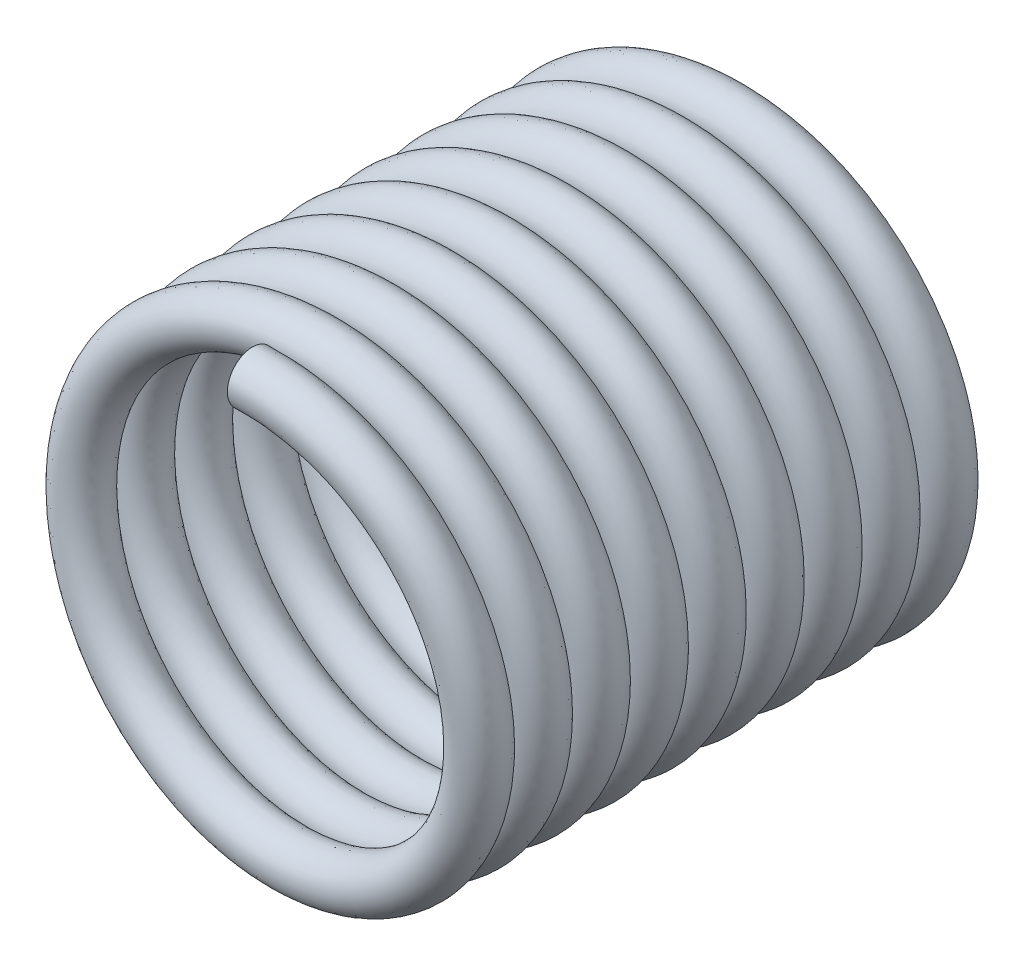
SolidWorks part; units mm, degrees
material "ASTM A36 Steel"
ref_plane "Front Plane" through (0, 0, 0) normal (0, 0, 1) x (1, 0, 0)
ref_plane "Top Plane" through (0, 0, 0) normal (0, 1, 0) x (1, 0, 0)
ref_plane "Right Plane" through (0, 0, 0) normal (1, 0, 0) x (0, 0, -1)
sketch "Sketch1" plane through (0, 0, 0) normal (0, 0, 1) x (1, 0, 0)
  circle A0 centre (0, 0) radius 4.0005
  dimension "D1" = 8.001
curve "Helix/Spiral1" pitch 1.1437 height 10.0076 turns 8.75
ref_plane "Plane1" through (0, 4.0005, 10.0076) normal (-0.999, 0, 0.0455) x (0.0454, -0.015, 0.9989)
sketch "Sketch2" plane through (0, 4.0005, 10.0076) normal (-0.999, 0, 0.0455) x (0.0454, -0.015, 0.9989)
  circle A0 centre (0.0016, 0.2066) radius 0.4953
  dimension "D1" = 0.9906
sweep "Sweep1" add profiles "Sketch2" path "Helix/Spiral1"
sketch "Sketch3" plane through (0, 4.0005, 10.0076) normal (-0.999, 0, 0.0455) x (0.0454, -0.015, 0.9989)
  circle A1 centre (0.0016, 0.2066) radius 0.4826
extrude "Boss-Extrude1" [suppressed] add sketch "Sketch3" along normal blind 34.925
sketch "Sketch4" plane through (0, 0, 0) normal (0, 0.999, -0.0455) x (1, 0, 0)
  circle A0 centre (-4.2071, -0.0047) radius 0.4953
  circle A1 centre (-4.2071, -0.0047) radius 0.4953 construction
extrude "Boss-Extrude2" [suppressed] add sketch "Sketch4" along normal blind 34.925
